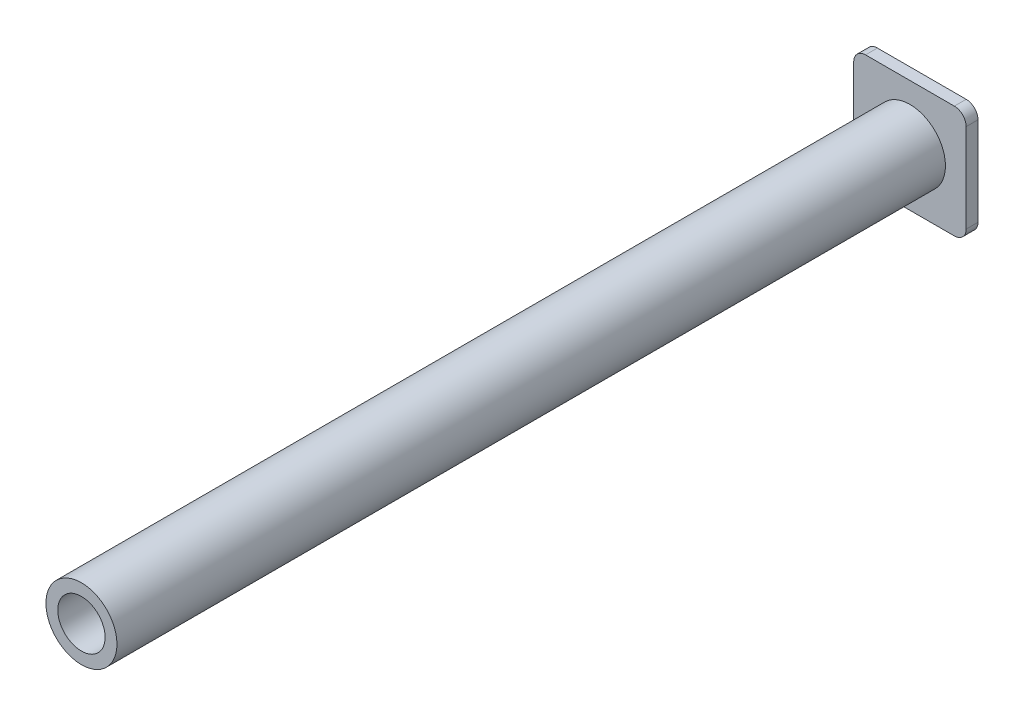
SolidWorks part; units mm, degrees
ref_plane "Front Plane" through (0, 0, 0) normal (0, 0, 1) x (1, 0, 0)
ref_plane "Top Plane" through (0, 0, 0) normal (0, 1, 0) x (1, 0, 0)
ref_plane "Right Plane" through (0, 0, 0) normal (1, 0, 0) x (0, 0, -1)
sketch "Plate Sketch" plane through (0, 0, 0) normal (0, 0, 1) x (1, 0, 0)
  line L1 (-47.5, 47.5) -> (47.5, 47.5)
  line L2 (-47.5, 47.5) -> (-47.5, -47.5)
  line L3 (-47.5, -47.5) -> (47.5, -47.5)
  line L4 (47.5, 47.5) -> (47.5, -47.5)
  line L5 (-47.5, 47.5) -> (47.5, -47.5) construction
  line L6 (-47.5, -47.5) -> (47.5, 47.5) construction
  point P0 (0, 0)
  dimension "D1" = 95
extrude "Plate Extrude" add sketch "Plate Sketch" along normal blind 10
fillet "Plate Fillet" radius 10 4 edges at (47.5, -47.5, 5) (-47.5, -47.5, 5) (-47.5, 47.5, 5) (47.5, 47.5, 5)
sketch "Pole Sketch" plane through (0, 0, 10) normal (0, 0, 1) x (1, 0, 0)
  circle A0 centre (0, 0) radius 30
  circle A1 centre (0, 0) radius 20
  dimension "D1" = 60
  dimension "D2" = 10
extrude "Pole Extrude" add sketch "Pole Sketch" along normal blind 700
